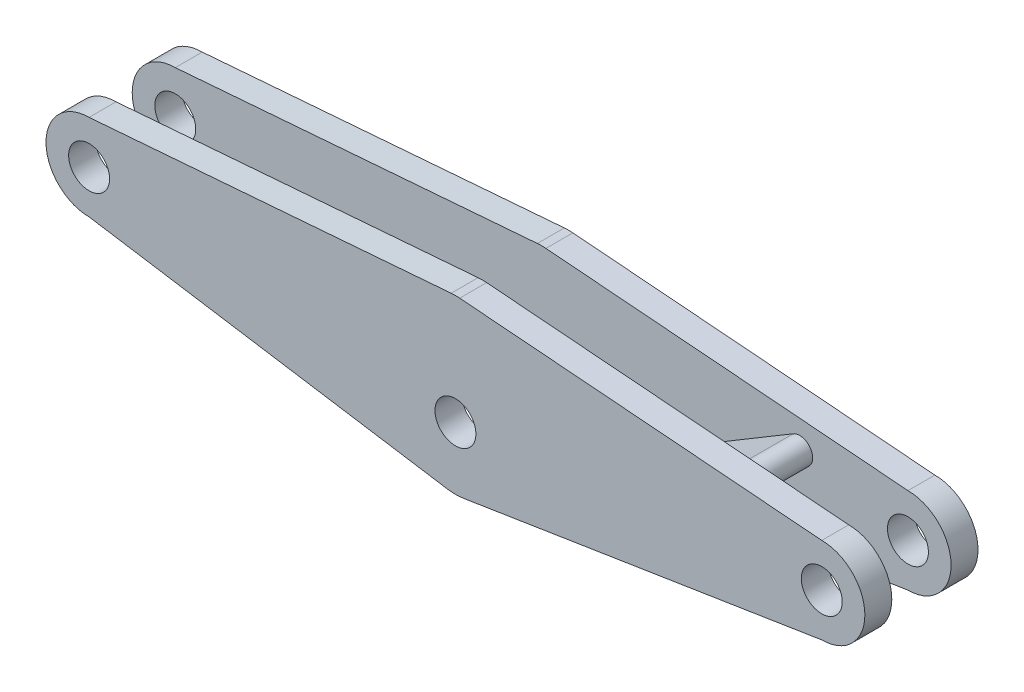
SolidWorks part; units mm, degrees
ref_plane "Front Plane" through (0, 0, 0) normal (0, 0, 1) x (1, 0, 0)
ref_plane "Top Plane" through (0, 0, 0) normal (0, 1, 0) x (1, 0, 0)
ref_plane "Right Plane" through (0, 0, 0) normal (1, 0, 0) x (0, 0, -1)
sketch "Sketch1" plane through (0, 0, 0) normal (0, 0, 1) x (1, 0, 0)
  line L0 (0, 3.35) -> (0, -4.65) construction
  line L1 (-17, 0) -> (17, 0) construction
  line L2 (17, 2) -> (0.1979, 3.3343)
  line L3 (17, -2) -> (0.3894, -4.6195)
  line L4 (-17, 2) -> (-0.1979, 3.3343)
  line L5 (-17, -2) -> (-0.3894, -4.6195)
  circle A0 centre (-17, 0) radius 0.95
  arc A1 (-17, 2) -> (-17, -2) centre (-17, 0) ccw
  circle A2 centre (17, 0) radius 0.95
  arc A3 (17, -2) -> (17, 2) centre (17, 0) ccw
  arc A4 (0.3894, -4.6195) -> (-0.3894, -4.6195) centre (0, -2.15) cw
  arc A5 (-0.1979, 3.3343) -> (0.1979, 3.3343) centre (0, 0.8421) cw
  circle A6 centre (0, -1.75) radius 0.95
  point P22 (0, -4.65)
  dimension "D5" = 4
  dimension "D6" = 1.9
  dimension "D7" = 4
  dimension "D8" = 1.9
  dimension "D9" = 2.5
  dimension "D11" = 1.9
  dimension "D2" = 17
  dimension "D3" = 8
  dimension "D4" = 3.35
  dimension "D10" = 1.75
extrude "Boss-Extrude1" add sketch "Sketch1" along normal mid plane 5.25
sketch "Sketch2" plane through (0.2644, 3.329, 0) normal (0.0792, 0.9969, 0) x (0.9969, -0.0792, 0)
  line L0 (18.9466, -2.625) -> (18.9466, 2.625) construction
  line L1 (-18.9466, 1.375) -> (18.9466, 1.375)
  line L2 (-18.9466, 1.375) -> (-18.9466, -1.375)
  line L3 (-18.9466, -1.375) -> (18.9466, -1.375)
  line L4 (18.9466, 1.375) -> (18.9466, -1.375)
  line L5 (-18.9466, 1.375) -> (18.9466, -1.375) construction
  line L6 (-18.9466, -1.375) -> (18.9466, 1.375) construction
  line L7 (-0.4612, 2.625) -> (-17.105, 2.625) construction
  point P0 (0, 0)
  dimension "D1" = 1.25
extrude "Cut-Extrude1" cut sketch "Sketch2" against normal mid plane 27.25
sketch "Sketch3" plane through (0, 0, 2.625) normal (0, 0, 1) x (1, 0, 0)
  line L0 (0, 0) -> (14.3345, 0.7835) construction
  line L1 (1.5441, 0.5351) -> (11.9782, 1.1054) construction
  line L2 (7, -1.8708) -> (11.9782, 1.1054) construction
  line L3 (6.6921, -1.3558) -> (11.6703, 1.6203)
  line L4 (7.3079, -2.3858) -> (12.2861, 0.5904)
  arc A0 (6.6921, -1.3558) -> (7.3079, -2.3858) centre (7, -1.8708) ccw
  arc A1 (12.2861, 0.5904) -> (11.6703, 1.6203) centre (11.9782, 1.1054) ccw
  point P6 (9.4891, -0.3827)
  dimension "D2" = 0.6
  dimension "D1" = 5.8
  dimension "D3" = 0.45
  dimension "D4" = 0.45
  dimension "D5" = 2.25
  dimension "D6" = 7
extrude "Boss-Extrude2" add sketch "Sketch3" against normal blind 5.25
